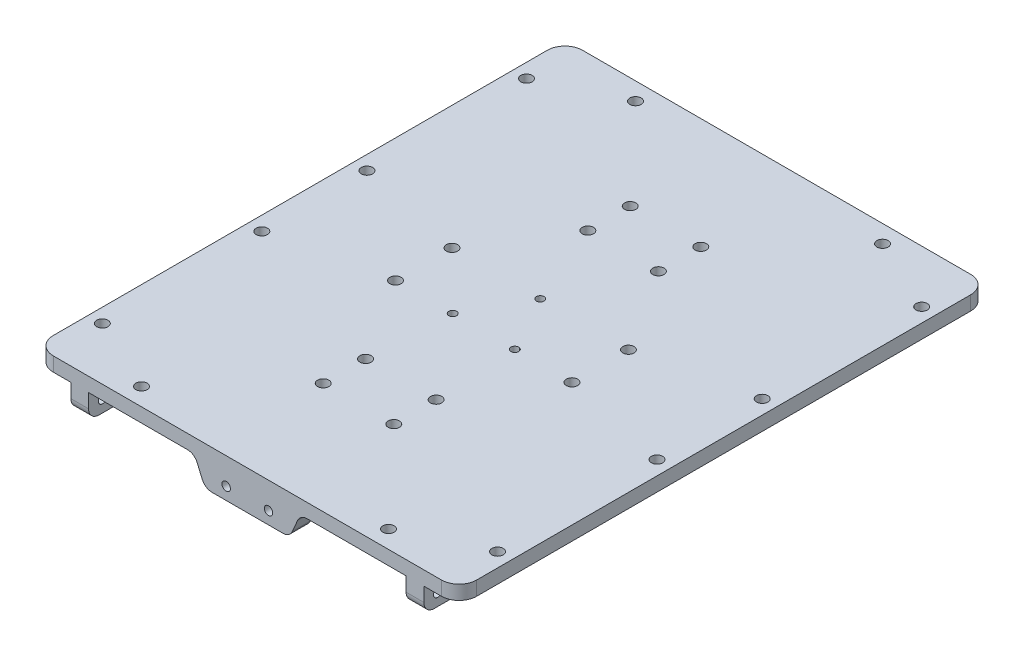
SolidWorks part; units mm, degrees
material "自定义塑料"
ref_plane "前视基准面" through (0, 0, 0) normal (0, 0, 1) x (1, 0, 0)
ref_plane "上视基准面" through (0, 0, 0) normal (0, 1, 0) x (1, 0, 0)
ref_plane "右视基准面" through (0, 0, 0) normal (1, 0, 0) x (0, 0, -1)
sketch "草图1" plane through (0, 0, 0) normal (0, 1, 0) x (1, 0, 0)
  line L0 (0, 0) -> (-20.2314, 0) construction
  line L1 (-60, 75) -> (60, 75)
  line L2 (-60, 75) -> (-60, -75)
  line L3 (-60, -75) -> (60, -75)
  line L4 (60, 75) -> (60, -75)
  line L5 (-60, 75) -> (60, -75) construction
  line L6 (-60, -75) -> (60, 75) construction
  line L7 (0, 0) -> (0, 21.0425) construction
  line L8 (-60, 37.5) -> (-53.3899, 37.5) construction
  circle A0 centre (-56, 60.1) radius 1.6
  circle A1 centre (-56, 14.9) radius 1.6
  circle A2 centre (-10, 43.5) radius 1.6
  circle A3 centre (-10, 31.5) radius 1.6
  circle A4 centre (-56, -14.9) radius 1.6
  circle A5 centre (-10, -31.5) radius 1.6
  circle A6 centre (-10, -43.5) radius 1.6
  circle A7 centre (-56, -60.1) radius 1.6
  circle A8 centre (56, -60.1) radius 1.6
  circle A9 centre (10, -43.5) radius 1.6
  circle A10 centre (10, -31.5) radius 1.6
  circle A11 centre (56, -14.9) radius 1.6
  circle A12 centre (56, 14.9) radius 1.6
  circle A13 centre (10, 31.5) radius 1.6
  circle A14 centre (10, 43.5) radius 1.6
  circle A15 centre (56, 60.1) radius 1.6
  circle A16 centre (0, 8) radius 1.1
  circle A17 centre (8.8, -8) radius 1.1
  circle A18 centre (-8.8, -8) radius 1.1
  circle A19 centre (-25, 8) radius 1.6
  circle A20 centre (25, 8) radius 1.6
  circle A21 centre (25, -8) radius 1.6
  circle A22 centre (-25, -8) radius 1.6
  circle A23 centre (35, 70) radius 1.6
  circle A24 centre (-35, 70) radius 1.6
  circle A25 centre (-35, -70) radius 1.6
  circle A26 centre (35, -70) radius 1.6
  point P0 (0, 0)
  dimension "D4" = 3.2
  dimension "D9" = 2.2
  dimension "D15" = 3.2
  dimension "D16" = 3.2
  dimension "D17" = 70
  dimension "D18" = 140
  dimension "D1" = 120
  dimension "D2" = 150
  dimension "D3" = 37.5
  dimension "D5" = 45.2
  dimension "D6" = 4
  dimension "D7" = 12
  dimension "D8" = 46
  dimension "D10" = 8
  dimension "D11" = 8
  dimension "D12" = 8.8
  dimension "D13" = 50
  dimension "D14" = 16
extrude "凸台-拉伸1" add sketch "草图1" along normal blind 4
ref_plane "基准面1" through (-50, 0, 0) normal (-1, 0, 0) x (0, 0, 1)
sketch "草图2" plane through (-50, 0, 0) normal (-1, 0, 0) x (0, 0, 1)
  line L0 (45, 0) -> (75, 0)
  line L1 (-75, 0) -> (75, 0) construction
  line L2 (75, 0) -> (75, -7)
  line L4 (57.1244, -7) -> (45, 0)
  line L5 (75, 4) -> (75, 0) construction
  line L6 (0, 31.7776) -> (0, -46.127) construction
  line L9 (-72.6356, 0) -> (-75, 0)
  line L11 (57.1244, -7) -> (75, -7)
  line L14 (-57.1244, -7) -> (-75, -7)
  line L15 (-57.1244, -7) -> (-45, 0)
  line L16 (-75, 0) -> (-75, -7)
  line L17 (-45, 0) -> (-75, 0)
  line L20 (-25, 0) -> (25, 0)
  line L21 (25, 0) -> (17, -7)
  line L23 (17, -7) -> (-17, -7)
  line L24 (-25, 0) -> (-17, -7)
  circle A6 centre (71, -3.5) radius 1.25
  circle A7 centre (-71, -3.5) radius 1.25
  circle A10 centre (65, -3.5) radius 1.25
  circle A11 centre (59, -3.5) radius 1.25
  circle A12 centre (-65, -3.5) radius 1.25
  circle A13 centre (-59, -3.5) radius 1.25
  point P33 (0, -7)
  point P34 (0, 0)
  dimension "D1" = 7
  dimension "D2" = 2.5
  dimension "D6" = 3.5
  dimension "D7" = 4
  dimension "D8" = 3
  dimension "D9" = 34
  dimension "D3" = 90
  dimension "D4" = 30
  dimension "D5" = 30
  dimension "D10" = 50
extrude "凸台-拉伸2" add sketch "草图2" against normal blind 5
ref_plane "基准面2" through (0, 0, 0) normal (-1, 0, 0) x (0, 0, 1)
mirror "镜向1" about plane through (0, 0, 0) normal (-1, 0, 0) of "凸台-拉伸2"
sketch "草图3" plane through (0, 0, 75) normal (0, 0, 1) x (1, 0, 0)
  line L0 (0, 17.4741) -> (0, -19.202) construction
  line L1 (-15, 0) -> (15, 0)
  line L2 (-45, 0) -> (45, 0) construction
  line L5 (-12, -7) -> (12, -7)
  line L6 (12, -7) -> (15, 0)
  line L7 (-12, -7) -> (-15, 0)
  circle A0 centre (6, -3.5) radius 1.2
  circle A1 centre (-6, -3.5) radius 1.2
  point P10 (0, -7)
  point P11 (0, 0)
  point P13 (0, 0)
  dimension "D5" = 2.4
  dimension "D6" = 12
  dimension "D1" = 30
  dimension "D2" = 24
  dimension "D3" = 7
  dimension "D4" = 3.5
extrude "凸台-拉伸3" add sketch "草图3" against normal blind 5
ref_plane "基准面3" through (0, 0, 0) normal (0, 0, 1) x (1, 0, 0)
mirror "镜向2" about plane through (0, 0, 0) normal (0, 0, 1) of "凸台-拉伸3"
fillet "圆角1" radius 5 4 edges at (-60, 2, -75) (60, 2, -75) (60, 2, 75) (-60, 2, 75)
fillet "圆角3" radius 3 28 edges at (-47.5, 0, 45) (-47.5, -7, 57.1244) (-47.5, -7, 75) (47.5, -7, 75) (47.5, -7, 57.1244) (47.5, 0, 45) (47.5, 0, -45) (-47.5, 0, -45) (47.5, -7, -75) (47.5, -7, -57.1244) (-47.5, -7, -57.1244) (-47.5, -7, -75) (-47.5, -7, 17) (-47.5, 0, 25) (-47.5, 0, -25) (-47.5, -7, -17) (47.5, 0, -25) (47.5, -7, -17) (47.5, -7, 17) (47.5, 0, 25) (-12, -7, -72.5) (-15, 0, -72.5) (12, -7, -72.5) (15, 0, -72.5) (-12, -7, 72.5) (-15, 0, 72.5) (12, -7, 72.5) (15, 0, 72.5)
